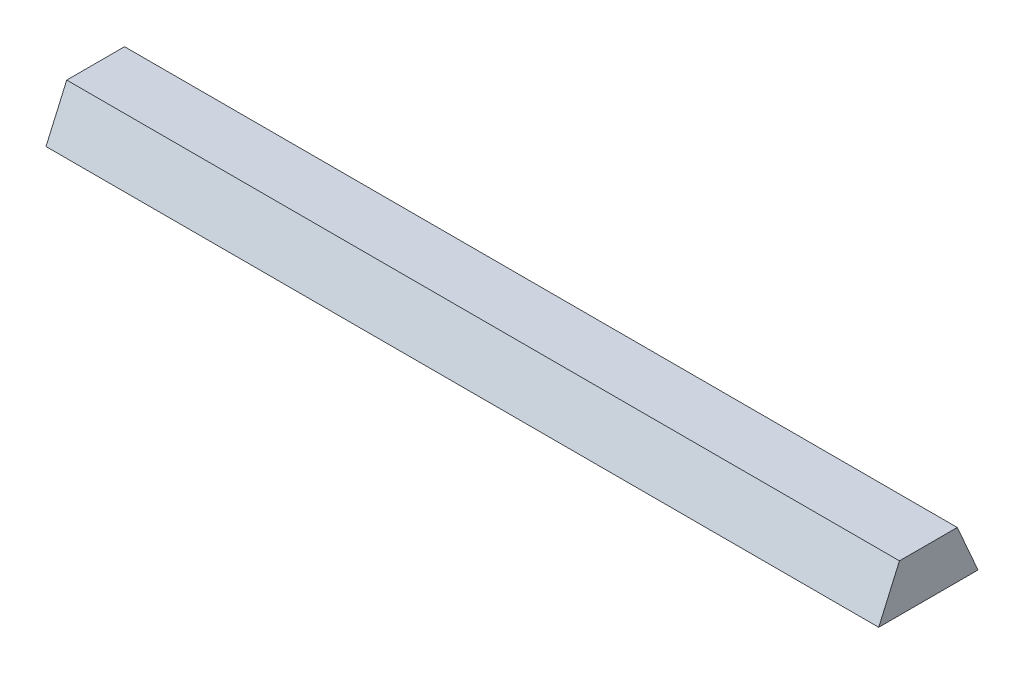
SolidWorks part; units mm, degrees
ref_plane "Alzado" through (0, 0, 0) normal (0, 0, 1) x (1, 0, 0)
ref_plane "Planta" through (0, 0, 0) normal (0, 1, 0) x (1, 0, 0)
ref_plane "Vista lateral" through (0, 0, 0) normal (1, 0, 0) x (0, 0, -1)
sketch "Croquis1" plane through (0, 0, 0) normal (1, 0, 0) x (0, 0, -1)
  line L0 (-12.5, 20.4064) -> (12.5, 20.4064)
  line L1 (-12.5, 20.4064) -> (-21.46, 0)
  line L2 (-21.46, 0) -> (21.46, 0)
  line L3 (21.46, 0) -> (12.5, 20.4064)
  line L4 (0, 20.4064) -> (0, 0) construction
  point P6 (0, 0)
  dimension "D1" = 25
  dimension "D2" = 42.92
extrude "Saliente-Extruir1" add sketch "Croquis1" along normal blind 360
